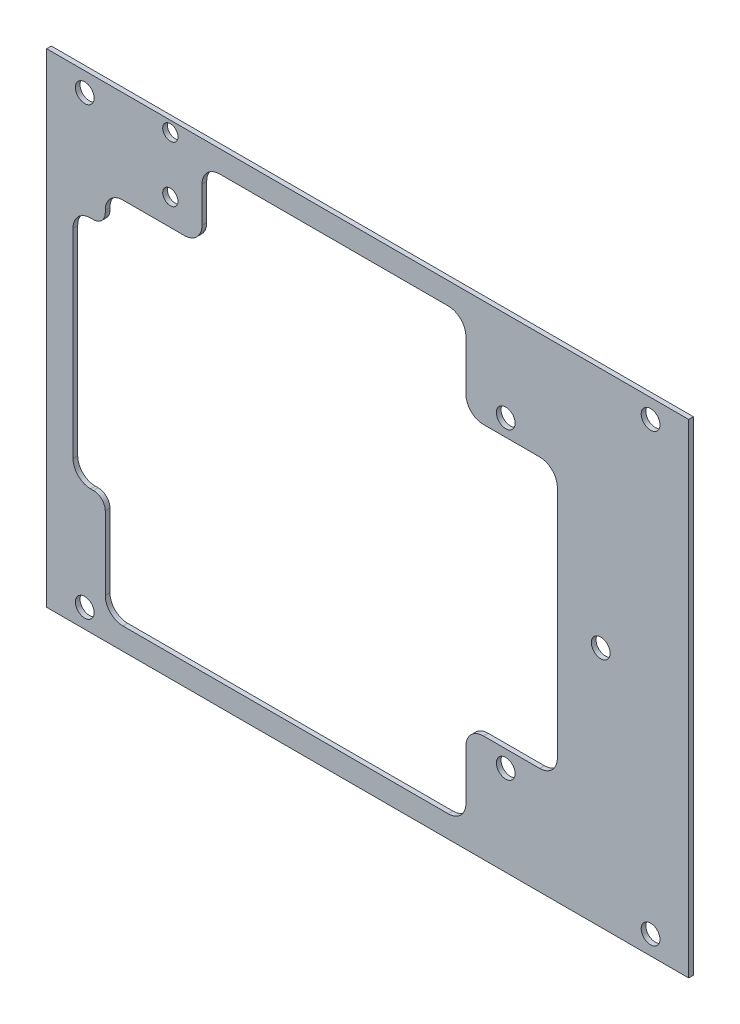
SolidWorks part; units mm, degrees
ref_plane "Front Plane" through (0, 0, 0) normal (0, 0, 1) x (1, 0, 0)
ref_plane "Top Plane" through (0, 0, 0) normal (0, 1, 0) x (1, 0, 0)
ref_plane "Right Plane" through (0, 0, 0) normal (1, 0, 0) x (0, 0, -1)
sketch "Sketch1" plane through (0, 0, 0) normal (0, 0, 1) x (1, 0, 0)
  line L0 (-50.25, -41.75) -> (-50.25, -61.75)
  line L1 (54.75, -83) -> (-54.75, -83)
  line L2 (54.75, -83) -> (54.75, -0.5)
  line L3 (54.75, -0.5) -> (-54.75, -0.5)
  line L4 (-54.75, -83) -> (-54.75, -0.5)
  line L5 (32.35, -18.75) -> (16.75, -18.75)
  line L6 (32.35, -64.75) -> (32.35, -18.75)
  line L7 (32.35, -64.75) -> (16.75, -64.75)
  line L8 (4.75, -41.75) -> (-48.75, -41.75) construction
  line L9 (-28.25, -4.25) -> (-28.25, -16.35)
  line L10 (-28.25, -16.35) -> (-44.75, -16.35)
  line L11 (-44.75, -16.35) -> (-44.75, -21.75)
  line L12 (-44.75, -79.25) -> (16.75, -79.25)
  line L13 (-50.25, -61.75) -> (-44.75, -61.75)
  line L14 (-44.75, -21.75) -> (-50.25, -21.75)
  line L15 (16.75, -18.75) -> (16.75, -4.25)
  line L16 (-50.25, -21.75) -> (-50.25, -41.75)
  line L17 (16.75, -64.75) -> (16.75, -79.25)
  line L18 (16.75, -4.25) -> (-28.25, -4.25)
  line L19 (-44.75, -61.75) -> (-44.75, -79.25)
  circle A0 centre (23.55, -67.625) radius 1.6
  circle A1 centre (23.55, -15.875) radius 1.6
  circle A2 centre (48.25, -3.75) radius 1.6
  circle A3 centre (48.25, -79.75) radius 1.6
  circle A4 centre (-48.25, -79.75) radius 1.6
  circle A5 centre (-48.25, -3.75) radius 1.6
  circle A6 centre (-33.65, -2.32) radius 1.3
  circle A7 centre (-33.65, -11.85) radius 1.3
  circle A8 centre (39.75, -41.75) radius 1.6
  dimension "D13" = 3.2
  dimension "D14" = 3.2
  dimension "D15" = 3.2
  dimension "D16" = 3.2
  dimension "D17" = 3.2
  dimension "D18" = 3.2
  dimension "D19" = 2.6
  dimension "D20" = 2.6
  dimension "D21" = 3.2
  dimension "D2" = 38
  dimension "D3" = 3.75
  dimension "D4" = 18.25
  dimension "D5" = 3.75
  dimension "D6" = 22.4
  dimension "D7" = 18.25
  dimension "D8" = 5.5
  dimension "D9" = 16.5
  dimension "D10" = 15.85
  dimension "D11" = 20
  dimension "D12" = 10
extrude "Boss-Extrude1" add sketch "Sketch1" along normal blind 0.8
fillet "Fillet1" radius 3 12 edges at (32.35, -18.75, 0.4) (16.75, -18.75, 0.4) (16.75, -4.25, 0.4) (-28.25, -4.25, 0.4) (-28.25, -16.35, 0.4) (-44.75, -16.35, 0.4) (-44.75, -79.25, 0.4) (16.75, -79.25, 0.4) (16.75, -64.75, 0.4) (32.35, -64.75, 0.4) (-50.25, -61.75, 0.4) (-50.25, -21.75, 0.4)
fillet "Fillet2" radius 2 2 edges at (-44.75, -61.75, 0.4) (-44.75, -21.75, 0.4)
